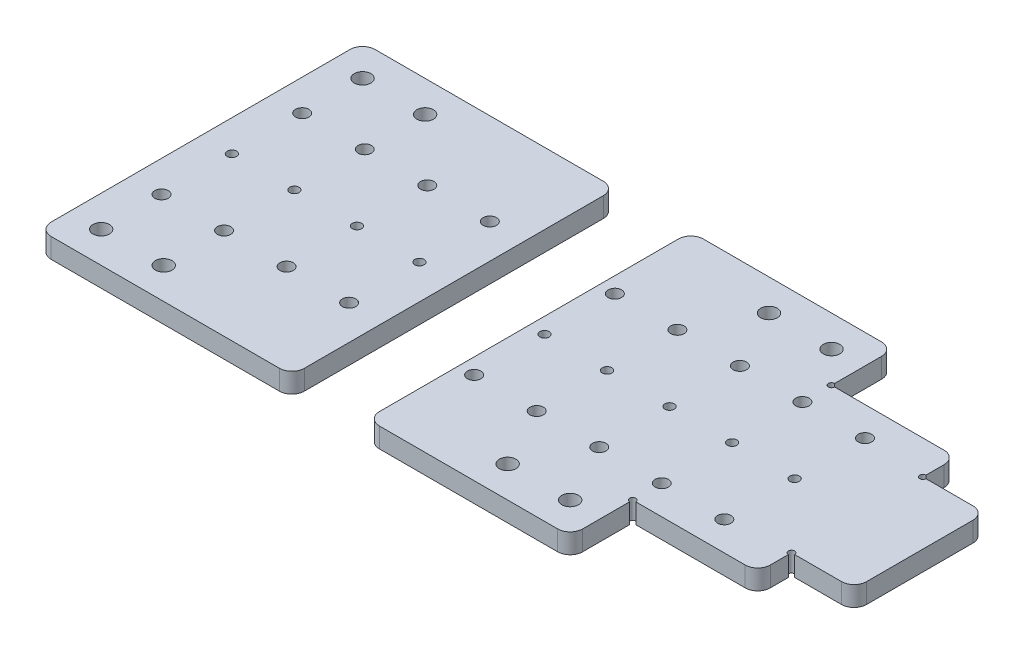
SolidWorks part; units mm, degrees
material "Acrylic (Medium-high impact)"
ref_plane "Front Plane" through (0, 0, 0) normal (0, 0, 1) x (1, 0, 0)
ref_plane "Top Plane" through (0, 0, 0) normal (0, 1, 0) x (1, 0, 0)
ref_plane "Right Plane" through (0, 0, 0) normal (1, 0, 0) x (0, 0, -1)
sketch "Sketch1" plane through (0, 0, 0) normal (0, 1, 0) x (1, 0, 0)
  line L0 (0, 103.6) -> (0, 83.6)
  line L1 (0, 0) -> (-170, 0)
  line L2 (40, 30.8) -> (40, 20)
  line L3 (0, 103.6) -> (-170, 103.6)
  line L4 (-170, 0) -> (-170, 103.6)
  line L5 (40, 72.8) -> (40, 30.8) construction
  line L7 (0, 20) -> (0, 0)
  line L8 (40, 72.8) -> (60, 72.8)
  line L9 (60, 72.8) -> (60, 30.8)
  line L10 (60, 30.8) -> (40, 30.8)
  line L11 (40, 72.8) -> (40, 83.6)
  line L12 (40, 83.6) -> (0, 83.6)
  line L13 (40, 20) -> (0, 20)
  dimension "D1" = 210
  dimension "D2" = 103.6
  dimension "D3" = 42
  dimension "D4" = 20
  dimension "D5" = 20
  dimension "D6" = 40
extrude "Boss-Extrude1" add sketch "Sketch1" along normal blind 6.35
sketch "Sketch2" plane through (0, 6.35, 0) normal (0, 1, 0) x (1, 0, 0)
  line L0 (-170, 93.6) -> (0, 93.6) construction
  line L1 (-170, 103.6) -> (-170, 0) construction
  line L2 (60, 30.8) -> (60, 72.8) construction
  line L3 (-85, 103.6) -> (-85, 0) construction
  line L4 (-170, 51.8) -> (60, 51.8) construction
  line L5 (0, 103.6) -> (-170, 103.6) construction
  line L6 (-170, 0) -> (0, 0) construction
  line L8 (-170, 74.3) -> (60, 74.3) construction
  circle A0 centre (-160, 93.6) radius 2.65
  circle A1 centre (-140, 93.6) radius 2.65
  circle A2 centre (-30, 93.6) radius 2.65
  circle A3 centre (-10, 93.6) radius 2.65
  circle A4 centre (-140, 10) radius 2.65
  circle A5 centre (-160, 10) radius 2.65
  circle A6 centre (-30, 10) radius 2.65
  circle A7 centre (-10, 10) radius 2.65
  circle A8 centre (-85, 93.6) radius 2.65
  circle A9 centre (-85, 10) radius 2.65
  circle A10 centre (-160, 74.3) radius 2.15
  circle A11 centre (-140, 74.3) radius 2.15
  circle A12 centre (-120, 74.3) radius 2.15
  circle A13 centre (-100, 74.3) radius 2.15
  circle A14 centre (-80, 74.3) radius 2.15
  circle A15 centre (-60, 74.3) radius 2.15
  circle A16 centre (-40, 74.3) radius 2.15
  circle A17 centre (-20, 74.3) radius 2.15
  circle A18 centre (0, 74.3) radius 2.15
  circle A19 centre (0, 29.3) radius 2.15
  circle A20 centre (-20, 29.3) radius 2.15
  circle A21 centre (-40, 29.3) radius 2.15
  circle A22 centre (-60, 29.3) radius 2.15
  circle A23 centre (-80, 29.3) radius 2.15
  circle A24 centre (-100, 29.3) radius 2.15
  circle A25 centre (-120, 29.3) radius 2.15
  circle A26 centre (-140, 29.3) radius 2.15
  circle A27 centre (-160, 29.3) radius 2.15
  circle A28 centre (-140, 51.8) radius 1.5
  circle A29 centre (-120, 51.8) radius 1.5
  circle A30 centre (-100, 51.8) radius 1.5
  circle A31 centre (-80, 51.8) radius 1.5
  circle A32 centre (-60, 51.8) radius 1.5
  circle A33 centre (-40, 51.8) radius 1.5
  circle A34 centre (-20, 51.8) radius 1.5
  circle A35 centre (0, 51.8) radius 1.5
  circle A36 centre (20, 74.3) radius 2.15
  circle A37 centre (20, 29.3) radius 2.15
  circle A38 centre (20, 51.8) radius 1.5
  circle A46 centre (-160, 51.8) radius 1.5
  dimension "D1" = 5.3
  dimension "D2" = 20
  dimension "D3" = 10
  dimension "D6" = 10
  dimension "D7" = 4.3
  dimension "D10" = 3
  dimension "D4" = 10
  dimension "D5" = 22.5
  dimension "D9" = 20
  dimension "D8" = 10
  dimension "D11" = 10
extrude "Cut-Extrude1" cut sketch "Sketch2" against normal through all
sketch "Sketch3" plane through (0, 6.35, 0) normal (0, 1, 0) x (1, 0, 0)
  circle A0 centre (0, 83.6) radius 1
  circle A1 centre (0, 20) radius 1
  circle A2 centre (40, 30.8) radius 1
  circle A3 centre (40, 72.8) radius 1
  dimension "D1" = 2
extrude "Cut-Extrude2" cut sketch "Sketch3" against normal through all
sketch "Sketch4" plane through (0, 6.35, 0) normal (0, 1, 0) x (1, 0, 0)
  line L0 (0, 103.6) -> (-170, 103.6) construction
  line L1 (-89, 103.6) -> (-65, 103.6)
  line L2 (-89, 103.6) -> (-89, 0)
  line L3 (-89, 0) -> (-65, 0)
  line L4 (-65, 103.6) -> (-65, 0)
  line L5 (-170, 0) -> (0, 0) construction
  circle A0 centre (-85, 93.6) radius 2.65 construction
  dimension "D1" = 4
  dimension "D2" = 20
extrude "Cut-Extrude3" cut sketch "Sketch4" against normal blind 10
fillet "Fillet1" radius 4 8 edges at (0, 3.175, 0) (40, 3.175, -20) (60, 3.175, -30.8) (60, 3.175, -72.8) (40, 3.175, -83.6) (0, 3.175, -103.6) (-65, 3.175, 0) (-65, 3.175, -103.6)
fillet "Fillet2" radius 4 4 edges at (-170, 3.175, -103.6) (-170, 3.175, 0) (-89, 3.175, 0) (-89, 3.175, -103.6)
